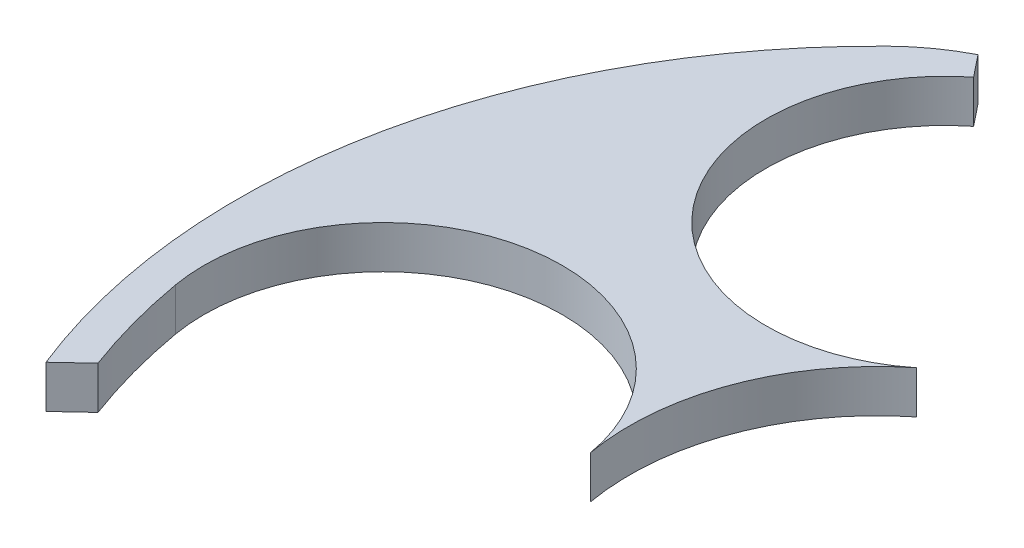
SolidWorks part; units mm, degrees
ref_plane "Plan de face" through (0, 0, 0) normal (0, 0, 1) x (1, 0, 0)
ref_plane "Plan de dessus" through (0, 0, 0) normal (0, 1, 0) x (1, 0, 0)
ref_plane "Plan de droite" through (0, 0, 0) normal (1, 0, 0) x (0, 0, -1)
sketch "Esquisse1" plane through (0, 0, 0) normal (0, 1, 0) x (1, 0, 0)
  line L0 (-85.9873, -39.219) -> (-82.8372, -36.2731)
  line L1 (-34.3894, 11.2538) -> (-62.5746, 46.649) construction
  line L2 (-62.5746, 46.649) -> (-60.5524, 44.1095)
  line L3 (-9.4508, 5.6286) -> (-14.9085, -3.5351) construction
  line L5 (3.3105, -15.9387) -> (9.4508, -5.6286) construction
  line L12 (0, 0) -> (-80, 0) construction
  line L13 (-64.4502, -24.994) -> (-51.2217, 24.3754) construction
  line L14 (-65, 0) -> (-64.4502, -24.994) construction
  arc A0 (-44.8834, -16.4709) -> (3.3105, -15.9387) centre (-21.2415, 25) ccw construction
  arc A1 (-19.5917, -4.1368) -> (-14.9085, -3.5351) centre (-17.486, -2) ccw construction
  arc A2 (-19.5917, -4.1368) -> (-34.3894, 11.2538) centre (258.274, 277.8334) cw construction
  arc A3 (-15.0496, 17.5397) -> (-22.3476, -39.7999) centre (-16.3245, -11.4322) ccw
  arc A4 (-86.2446, -23.7683) -> (-82.8372, -36.2731) centre (-16.3245, -11.4322) ccw
  arc A36 (-51.2217, 24.3754) -> (-64.4502, -24.994) centre (-16.3245, -11.4322) ccw construction
  arc A37 (-68.6703, 42.2792) -> (-85.9873, -39.219) centre (-16.3245, -11.4322) ccw
  arc A41 (9.4508, -5.6286) -> (-9.4508, 5.6286) centre (0, 0) ccw construction
  arc A42 (-16.402, 38.5677) -> (-47.4539, -50.5598) centre (-16.3245, -11.4322) ccw construction
  arc A43 (-60.5524, 44.1095) -> (-34.3894, 11.2538) centre (-47.4709, 27.6817) ccw
  arc A44 (-62.5746, 46.649) -> (-68.6703, 42.2792) centre (-51.2217, 24.3754) ccw
  arc A45 (-44.8834, -16.4709) -> (-86.2446, -23.7683) centre (-65.564, -20.1196) ccw
  point P78 (-56.6847, 2.6915)
  point P85 (-65, 0)
  dimension "D4" = 25
  dimension "D5" = 12
  dimension "D6" = 21
  dimension "D8" = 25
  dimension "D10" = 3
  dimension "D11" = 17.6
  dimension "D18" = 80
  dimension "D20" = 75
  dimension "D26" = 11
  dimension "D13" = 50
  dimension "D14" = 21
  dimension "D12" = 2
  dimension "D22" = 25
  dimension "D23" = 75
  dimension "D24" = 28
  dimension "D25" = 15
  dimension "D30" = 5
  dimension "D32" = 5
extrude "Boss.-Extru.1" add sketch "Esquisse1" along normal blind 5 contours A45 A3 A43 A44 A37 L0
